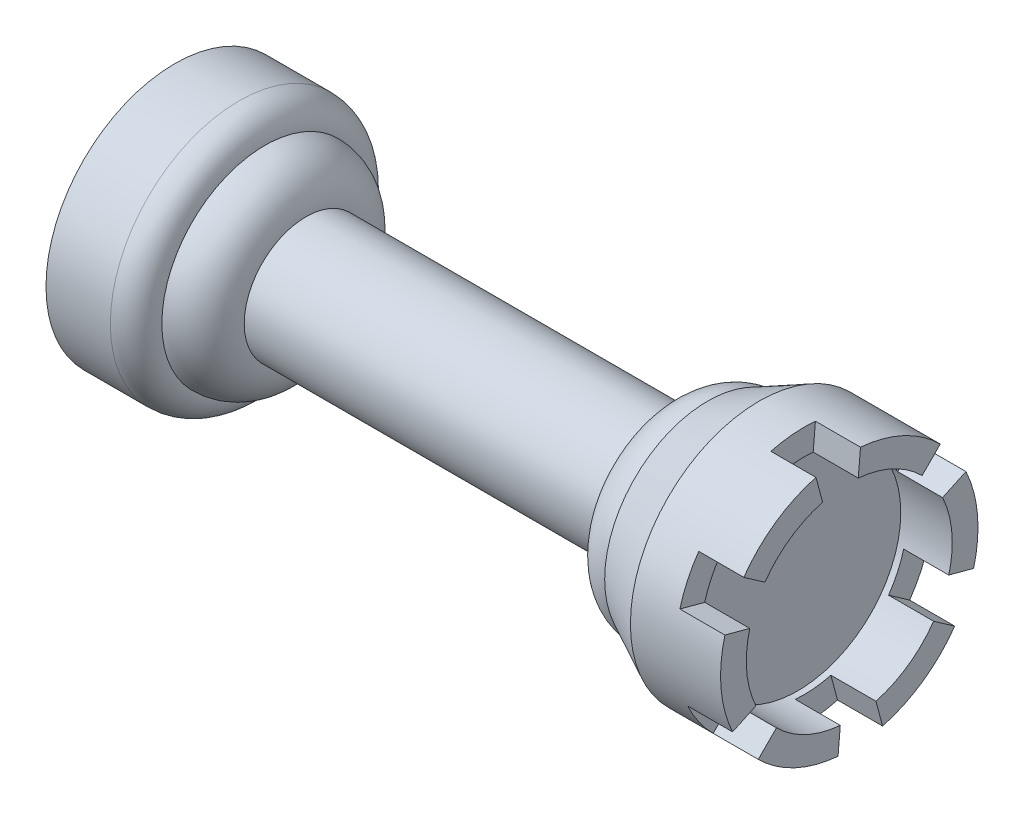
SolidWorks part; units mm, degrees
ref_plane "Спереди" through (0, 0, 0) normal (0, 0, 1) x (1, 0, 0)
ref_plane "Сверху" through (0, 0, 0) normal (0, 1, 0) x (1, 0, 0)
ref_plane "Справа" through (0, 0, 0) normal (1, 0, 0) x (0, 0, -1)
sketch "попа" plane through (0, 0, 0) normal (0, 0, 1) x (1, 0, 0)
  line L0 (0, 0) -> (0, 10)
  line L1 (0, 10) -> (5, 10)
  line L2 (5, 10) -> (5, 0) construction
  line L3 (0, 0) -> (10.2, 0)
  line L4 (28.82, 0) -> (-28.82, 0) construction
  line L5 (7, 8) -> (7, 0)
  line L6 (10.2, 4.8) -> (10.2, 0)
  line L7 (1, 0) -> (1, 5.25)
  line L8 (1, 5.25) -> (3.5, 5.25)
  line L9 (3.5, 5.25) -> (3.5, 0)
  arc A0 (5, 10) -> (7, 8) centre (5, 8) cw
  arc A1 (7, 8) -> (10.2, 4.8) centre (7, 4.8) cw
  dimension "D3" = 2
  dimension "D4" = 3.2
  dimension "D1" = 10
  dimension "D2" = 5
  dimension "D5" = 4.8
  dimension "D6" = 1
  dimension "D7" = 2.5
  dimension "D8" = 5.25
sketch "верх" plane through (0, 0, 0) normal (0, 0, 1) x (1, 0, 0)
  line L0 (10.2, 4.8) -> (38.2, 4.8)
  line L1 (38.2, 4.8) -> (38.2, 0)
  line L3 (41.4, 0) -> (41.4, 8)
  line L5 (55, 0) -> (-55, 0) construction
  line L8 (10.2, 0) -> (45.4, 0)
  line L9 (10.2, 4.8) -> (10.2, 0)
  line L10 (45.4, 0) -> (45.4, 10)
  line L11 (41.4, 8) -> (45.4, 10)
  arc A0 (38.2, 4.8) -> (41.4, 8) centre (41.4, 4.8) cw
  dimension "D2" = 4.8
  dimension "D3" = 3.2
  dimension "D4" = 8
  dimension "D5" = 3.2
  dimension "D1" = 28
  dimension "D6" = 4
  dimension "D7" = 10
revolve "Повернуть4" add sketch "верх" angle 360 about L8
revolve "Повернуть6" add sketch "попа" angle 360 about L3
sketch "крона" plane through (0, 0, 0) normal (0, 0, 1) x (1, 0, 0)
  line L0 (45.4, 10) -> (52.4, 10)
  line L1 (52.4, 10) -> (52.4, 0)
  line L2 (52.4, 0) -> (45.4, 0)
  line L3 (55, 0) -> (-55, 0) construction
  line L4 (45.4, 0) -> (45.4, 10)
  dimension "D1" = 7
revolve "Повернуть7" add sketch "крона" angle 360 about L2
sketch "Эскиз18" plane through (52.4, 0, 0) normal (1, 0, 0) x (0, 0, -1)
  circle A0 centre (0, 0) radius 8
  dimension "D1" = 16
extrude "Вырез-Вытянуть4" cut sketch "Эскиз18" against normal blind 4
sketch "Эскиз19" plane through (52.4, 0, 0) normal (1, 0, 0) x (0, 0, -1)
  line L0 (0, 0) -> (-9.6593, 2.5882) construction
  line L1 (0, 0) -> (-8.1915, 5.7358) construction
  line L2 (55, 0) -> (-55, 0) construction
  line L5 (-8.1915, 5.7358) -> (-6.5532, 4.5886)
  line L6 (-9.6593, 2.5882) -> (-7.7274, 2.0706)
  line L7 (-2.5882, 9.6593) -> (-2.0706, 7.7274)
  line L8 (0.8716, 9.9619) -> (0.6972, 7.9696)
  line L9 (7.0711, 7.0711) -> (5.6569, 5.6569)
  line L10 (9.0631, 4.2262) -> (7.2505, 3.3809)
  line L11 (9.6593, -2.5882) -> (7.7274, -2.0706)
  line L12 (8.1915, -5.7358) -> (6.5532, -4.5886)
  line L13 (2.5882, -9.6593) -> (2.0706, -7.7274)
  line L14 (-0.8716, -9.9619) -> (-0.6972, -7.9696)
  line L15 (-7.0711, -7.0711) -> (-5.6569, -5.6569)
  line L16 (-9.0631, -4.2262) -> (-7.2505, -3.3809)
  circle A0 centre (0, 0) radius 10 construction
  arc A4 (-9.6593, 2.5882) -> (-8.1915, 5.7358) centre (0, 0) cw
  arc A5 (-7.7274, 2.0706) -> (-6.5532, 4.5886) centre (0, 0) cw
  circle A6 centre (0, 0) radius 8 construction
  arc A7 (-2.0706, 7.7274) -> (0.6972, 7.9696) centre (0, 0) cw
  arc A8 (-2.5882, 9.6593) -> (0.8716, 9.9619) centre (0, 0) cw
  arc A9 (5.6569, 5.6569) -> (7.2505, 3.3809) centre (0, 0) cw
  arc A10 (7.0711, 7.0711) -> (9.0631, 4.2262) centre (0, 0) cw
  arc A11 (7.7274, -2.0706) -> (6.5532, -4.5886) centre (0, 0) cw
  arc A12 (9.6593, -2.5882) -> (8.1915, -5.7358) centre (0, 0) cw
  arc A13 (2.0706, -7.7274) -> (-0.6972, -7.9696) centre (0, 0) cw
  arc A14 (2.5882, -9.6593) -> (-0.8716, -9.9619) centre (0, 0) cw
  arc A15 (-5.6569, -5.6569) -> (-7.2505, -3.3809) centre (0, 0) cw
  arc A16 (-7.0711, -7.0711) -> (-9.0631, -4.2262) centre (0, 0) cw
  point P36 (0, 0)
  dimension "D3" = 6
  dimension "D1" = 15
  dimension "D2" = 35
extrude "Вырез-Вытянуть5" cut sketch "Эскиз19" against normal blind 3.5
